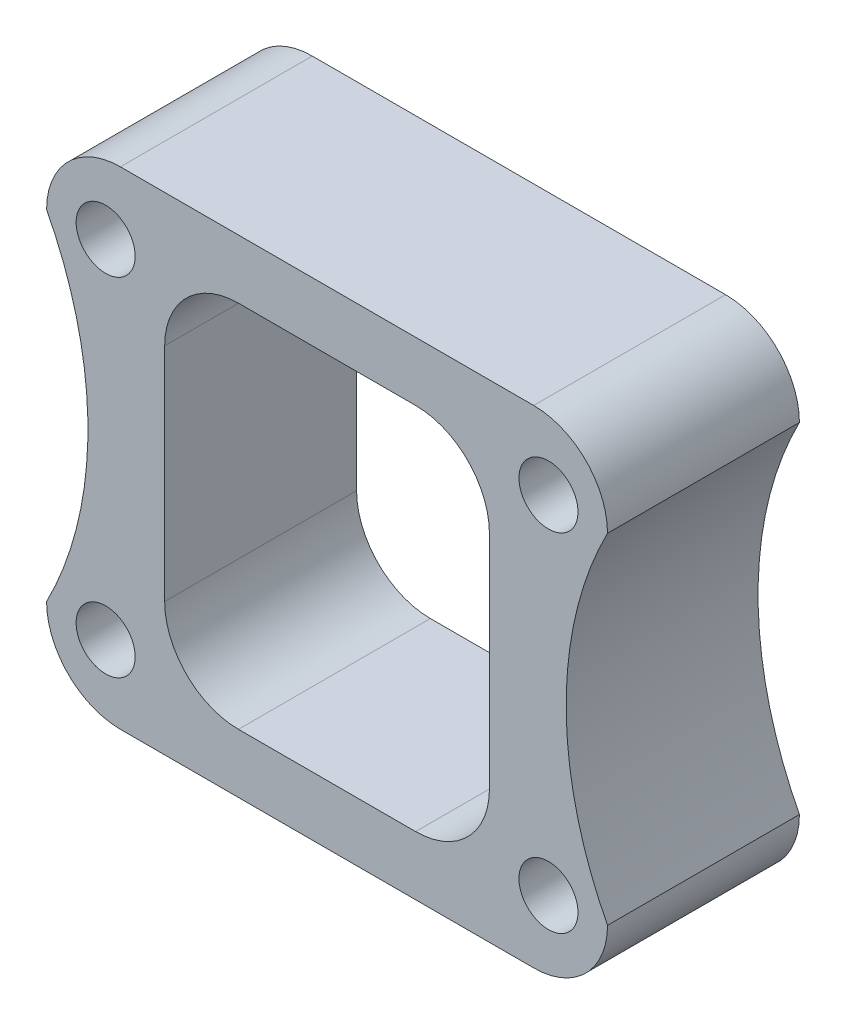
SolidWorks part; units mm, degrees
ref_plane "Alzado" through (0, 0, 0) normal (0, 0, 1) x (1, 0, 0)
ref_plane "Planta" through (0, 0, 0) normal (0, 1, 0) x (1, 0, 0)
ref_plane "Vista lateral" through (0, 0, 0) normal (1, 0, 0) x (0, 0, -1)
sketch "Croquis1" plane through (0, 0, 0) normal (0, 0, 1) x (1, 0, 0)
  line L1 (5, 0) -> (33, 0)
  line L3 (5, 33) -> (33, 33)
  circle A0 centre (4, 4.75) radius 2
  circle A1 centre (34, 4.75) radius 2
  circle A2 centre (34, 28.25) radius 2
  circle A3 centre (4, 28.25) radius 2
  arc A4 (5, 33) -> (0, 28) centre (5, 28) ccw
  arc A5 (38, 28) -> (33, 33) centre (33, 28) ccw
  arc A6 (5, 0) -> (0, 5) centre (5, 5) cw
  arc A7 (38, 5) -> (33, 0) centre (33, 5) cw
  arc A8 (0, 28) -> (0, 5) centre (-22.198, 16.5) cw
  arc A9 (38, 28) -> (38, 5) centre (60.198, 16.5) ccw
  point P9 (0, 33)
  point P18 (38, 33)
  point P21 (0, 0)
  dimension "D1" = 4
  dimension "D8" = 5
  dimension "D9" = 5
  dimension "D10" = 5
  dimension "D11" = 5
  dimension "D12" = 25
  dimension "D13" = 25
  dimension "D2" = 38
  dimension "D3" = 33
  dimension "D5" = 4.75
  dimension "D6" = 2
  dimension "D7" = 2
extrude "Saliente-Extruir1" add sketch "Croquis1" along normal blind 13
sketch "Croquis2" plane through (0, 0, 0) normal (0, 0, -1) x (-1, 0, 0)
  line L0 (-19, 0) -> (-19, 33) construction
  line L1 (-5, 0) -> (-33, 0) construction
  line L2 (-33, 33) -> (-5, 33) construction
  line L3 (-30, 4) -> (-30, 29)
  line L4 (-30, 4) -> (-8, 4)
  line L5 (-30, 29) -> (-8, 29)
  line L6 (-8, 4) -> (-8, 29)
  line L7 (-30, 4) -> (-8, 29) construction
  line L8 (-30, 29) -> (-8, 4) construction
  point P6 (-19, 16.5)
  point P7 (-19, 16.5)
  dimension "D1" = 22
  dimension "D2" = 25
extrude "Cortar-Extruir1" cut sketch "Croquis2" against normal through all
fillet "Redondeo1" radius 5 4 edges at (8, 4, 6.5) (30, 4, 6.5) (30, 29, 6.5) (8, 29, 6.5)
